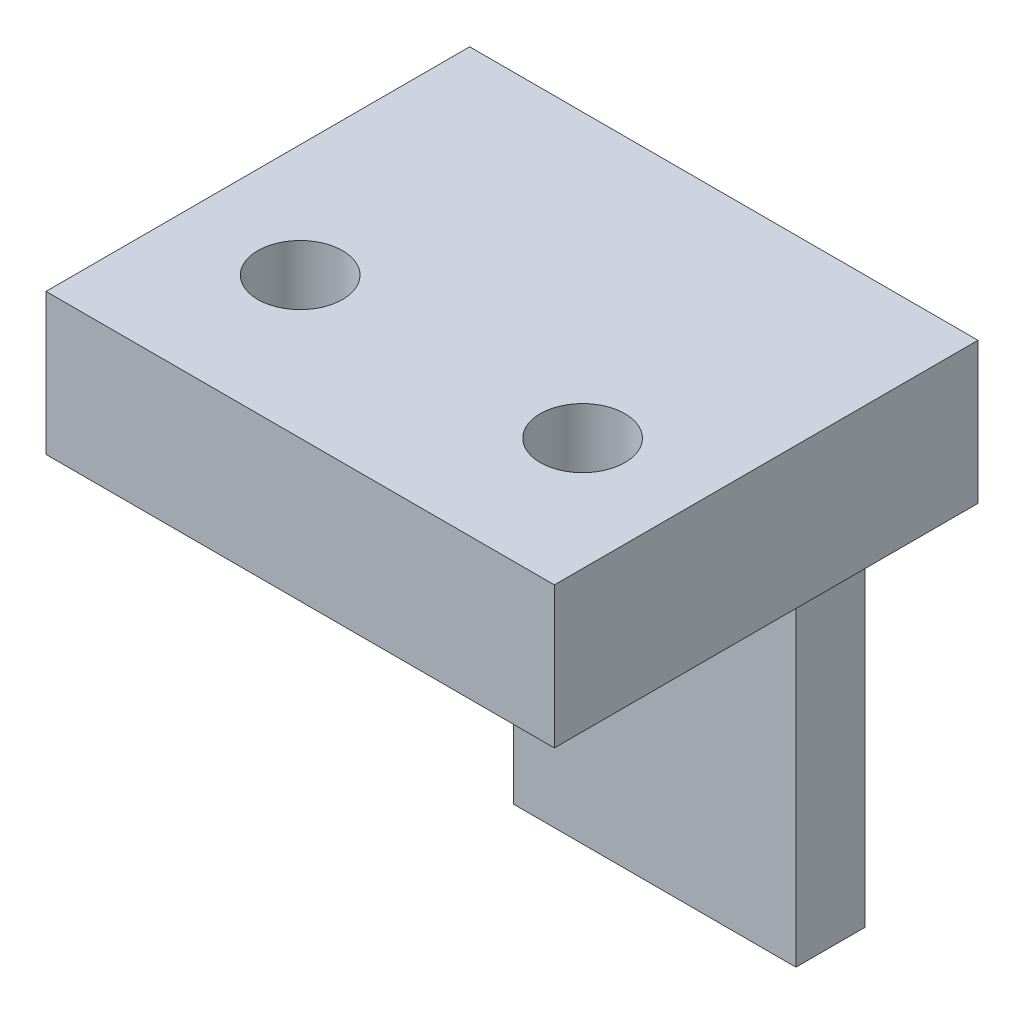
SolidWorks part; units mm, degrees
ref_plane "Front Plane" through (0, 0, 0) normal (0, 0, 1) x (1, 0, 0)
ref_plane "Top Plane" through (0, 0, 0) normal (0, 1, 0) x (1, 0, 0)
ref_plane "Right Plane" through (0, 0, 0) normal (1, 0, 0) x (0, 0, -1)
sketch "Sketch1" plane through (0, 0, 0) normal (0, 1, 0) x (1, 0, 0)
  line L0 (0, 0) -> (-5, 0) construction
  line L1 (9, 5) -> (-9, 5)
  line L2 (9, 5) -> (9, -5)
  line L3 (9, -5) -> (-9, -5)
  line L4 (-9, 5) -> (-9, -5)
  line L5 (9, 5) -> (-9, -5) construction
  line L6 (9, -5) -> (-9, 5) construction
  line L7 (0, 0) -> (5, 0) construction
  circle A0 centre (-5, 0) radius 1.5
  circle A1 centre (5, 0) radius 1.5
  point P0 (0, 0)
extrude "Boss-Extrude1" add sketch "Sketch1" along normal blind 5
sketch "Sketch2" plane through (0, 0, -5) normal (0, 0, -1) x (-1, 0, 0)
  line L1 (-9, 5) -> (9, 5)
  line L2 (-9, 5) -> (-9, 0)
  line L3 (-9, 0) -> (9, 0)
  line L4 (9, 5) -> (9, 0)
extrude "Boss-Extrude2" add sketch "Sketch2" along normal blind 5
sketch "Sketch3" plane through (0, 0, 0) normal (0, -1, 0) x (1, 0, 0)
  line L1 (9, -10) -> (-9, -10) construction
  line L2 (5, -7.5527) -> (-5, -7.5527)
  line L3 (5, -7.5527) -> (5, -10)
  line L4 (5, -10) -> (-5, -10)
  line L5 (-5, -7.5527) -> (-5, -10)
  line L6 (5, -7.5527) -> (-5, -10) construction
  line L7 (5, -10) -> (-5, -7.5527) construction
  point P0 (0, -8.7763)
  point P6 (0, -10)
  dimension "D1" = 0
  dimension "D2" = 0
extrude "Boss-Extrude3" add sketch "Sketch3" along normal blind 15
sketch "Sketch4" plane through (5, 0, 0) normal (1, 0, 0) x (0, 0, -1)
  line L6 (4.5527, 0) -> (7.5527, 0)
  line L7 (7.5527, 0) -> (7.5527, -3)
  arc A0 (7.5527, -3) -> (4.5527, 0) centre (4.5527, -3) ccw
  point P11 (7.5527, 0)
  point P12 (7.5527, 0)
  dimension "D1" = 3
extrude "Boss-Extrude5" add sketch "Sketch4" against normal blind 10
